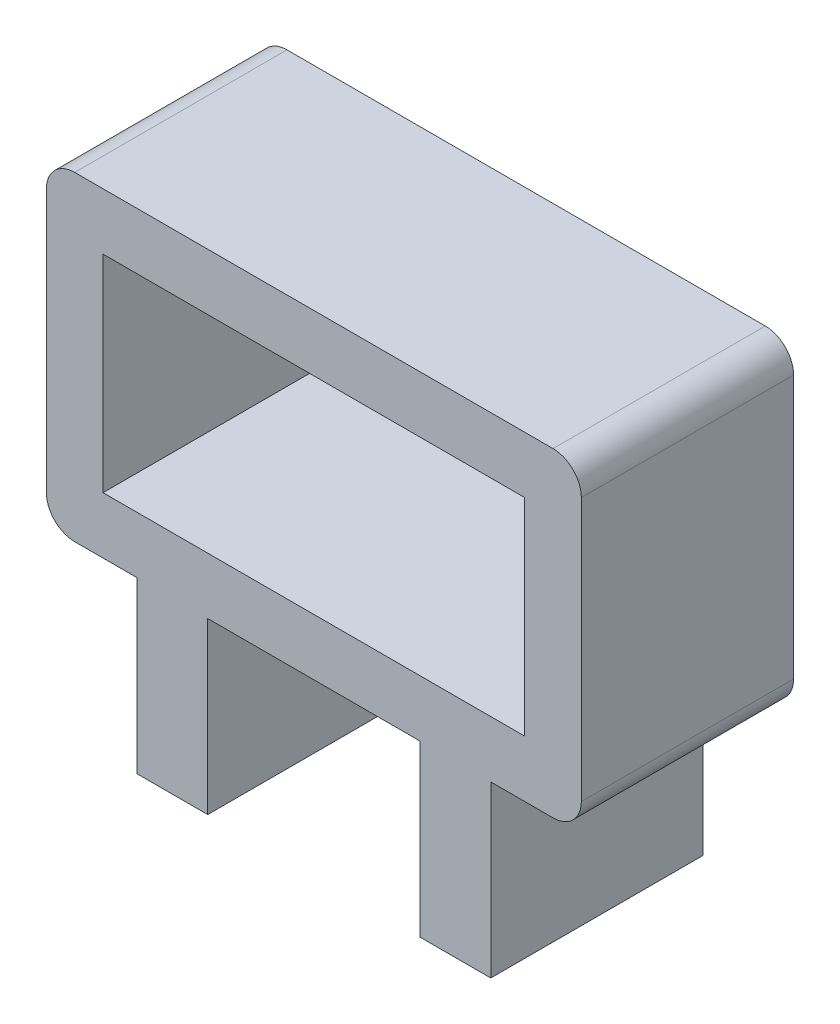
SolidWorks part; units mm, degrees
ref_plane "Front Plane" through (0, 0, 0) normal (0, 0, 1) x (1, 0, 0)
ref_plane "Top Plane" through (0, 0, 0) normal (0, 1, 0) x (1, 0, 0)
ref_plane "Right Plane" through (0, 0, 0) normal (1, 0, 0) x (0, 0, -1)
sketch "Sketch1" plane through (0, 0, 0) normal (0, 0, 1) x (1, 0, 0)
  line L0 (-17.2047, -1.2442) -> (-17.2047, -14.163) construction
  line L1 (-32.1047, 16.437) -> (-2.3047, 16.437)
  line L2 (-32.1047, 16.437) -> (-32.1047, 1.837)
  line L3 (-32.1047, 1.837) -> (-2.3047, 1.837)
  line L4 (-2.3047, 16.437) -> (-2.3047, 1.837)
  line L5 (-32.1047, 16.437) -> (-2.3047, 1.837) construction
  line L6 (-32.1047, 1.837) -> (-2.3047, 16.437) construction
  line L7 (-36.1047, 20.437) -> (1.6953, 20.437)
  line L8 (-36.1047, 20.437) -> (-36.1047, -2.163)
  line L9 (-36.1047, -2.163) -> (-29.7047, -2.163)
  line L10 (1.6953, 20.437) -> (1.6953, -2.163)
  line L11 (-36.1047, 20.437) -> (1.6953, -2.163) construction
  line L12 (-36.1047, -2.163) -> (1.6953, 20.437) construction
  line L13 (-17.2047, -14.163) -> (-9.7047, -14.163) construction
  line L14 (-9.7047, -14.163) -> (-37.3847, -14.163) construction
  line L15 (-24.7047, -2.163) -> (-24.7047, -28.6913) construction
  line L16 (-9.7047, -2.163) -> (-9.7047, -29.3241) construction
  line L17 (-24.7047, -2.163) -> (-24.7047, -14.163)
  line L18 (-24.7047, -14.163) -> (-29.7047, -14.163)
  line L19 (-29.7047, -14.163) -> (-29.7047, -2.163)
  line L20 (-9.7047, -2.163) -> (-9.7047, -14.163)
  line L22 (-4.7047, -14.163) -> (-4.7047, -2.163)
  line L23 (-24.7047, -2.163) -> (-9.7047, -2.163)
  line L24 (-4.7047, -2.163) -> (1.6953, -2.163)
  line L25 (-9.7047, -14.163) -> (-4.7047, -14.163)
  point P0 (-17.2047, 9.137)
  point P6 (-17.2047, 9.137)
  dimension "D1" = 7.5
  dimension "D2" = 7.5
  dimension "D3" = 14.6
  dimension "D4" = 29.8
  dimension "D5" = 12
  dimension "D6" = 5
  dimension "D7" = 5
extrude "Boss-Extrude1" add sketch "Sketch1" along normal blind 15
fillet "Fillet1" radius 2 4 edges at (-36.1047, -2.163, 7.5) (1.6953, -2.163, 7.5) (-36.1047, 20.437, 7.5) (1.6953, 20.437, 7.5)
